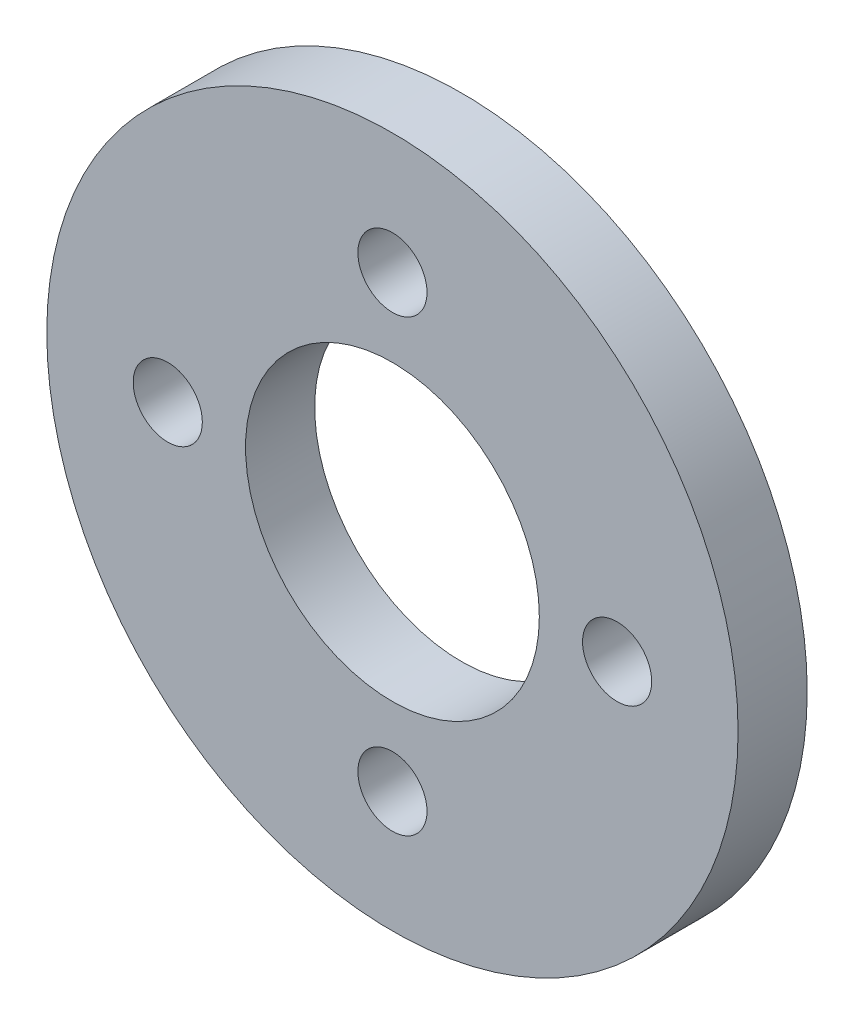
SolidWorks part; units mm, degrees
ref_plane "Front Plane" through (0, 0, 0) normal (0, 0, 1) x (1, 0, 0)
ref_plane "Top Plane" through (0, 0, 0) normal (0, 1, 0) x (1, 0, 0)
ref_plane "Right Plane" through (0, 0, 0) normal (1, 0, 0) x (0, 0, -1)
sketch "Sketch1" plane through (0, 0, 0) normal (0, 0, 1) x (1, 0, 0)
  circle A0 centre (0, 0) radius 4.25
  circle A1 centre (0, 0) radius 10
  dimension "D1" = 20
  dimension "D2" = 8.5
extrude "Boss-Extrude1" add sketch "Sketch1" along normal blind 2
sketch "Sketch2" plane through (0, 0, 2) normal (0, 0, 1) x (1, 0, 0)
  line L0 (-11.6054, 0) -> (13.4104, 0) construction
  line L1 (0, 11.0695) -> (0, -12.0848) construction
  circle A0 centre (-6.5, 0) radius 1
  dimension "D3" = 2
  dimension "D1" = 25.0158
  dimension "D2" = 23.1544
  dimension "D4" = 6.5
extrude "Cut-Extrude1" cut sketch "Sketch2" against normal up to surface (2 mm away) up to face at (10, 0, 0)
pattern_circular "CirPattern1" count 4 over 360 about axis through (0, 0, 0) along (0, 0, 1) of "Cut-Extrude1"
